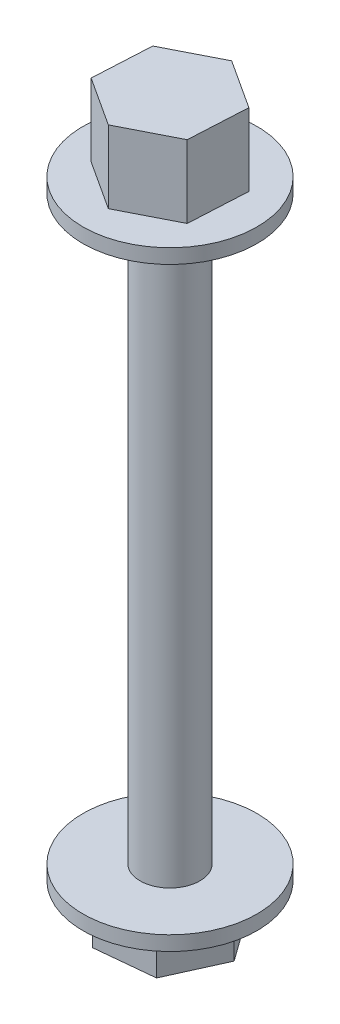
SolidWorks part; units mm, degrees
material "Plain Carbon Steel"
ref_plane "Front Plane" through (0, 0, 0) normal (0, 0, 1) x (1, 0, 0)
ref_plane "Top Plane" through (0, 0, 0) normal (0, 1, 0) x (1, 0, 0)
ref_plane "Right Plane" through (0, 0, 0) normal (1, 0, 0) x (0, 0, -1)
sketch "Sketch1" plane through (0, 0, 0) normal (0, 1, 0) x (1, 0, 0)
  circle A0 centre (0, 0) radius 3.2639
  dimension "D1" = 6.5278
extrude "Boss-Extrude1" add sketch "Sketch1" along normal blind 63.5
sketch "Sketch2" plane through (0, 63.5, 0) normal (0, 1, 0) x (1, 0, 0)
  circle A0 centre (0, 0) radius 9.525
  dimension "D1" = 19.05
extrude "Boss-Extrude2" add sketch "Sketch2" along normal blind 1.5875
sketch "Sketch3" plane through (0, 0, 0) normal (0, -1, 0) x (1, 0, 0)
  circle A0 centre (0, 0) radius 9.525
  dimension "D1" = 19.05
extrude "Boss-Extrude3" add sketch "Sketch3" along normal blind 1.5875
sketch "Sketch4" plane through (0, -1.5875, 0) normal (0, -1, 0) x (1, 0, 0)
  line L1 (3.7399, 5.2131) -> (-2.6447, 5.8453)
  line L2 (-2.6447, 5.8453) -> (-6.3846, 0.6323)
  line L3 (-6.3846, 0.6323) -> (-3.7399, -5.2131)
  line L4 (-3.7399, -5.2131) -> (2.6447, -5.8453)
  line L5 (2.6447, -5.8453) -> (6.3846, -0.6323)
  line L6 (6.3846, -0.6323) -> (3.7399, 5.2131)
  circle A0 centre (0, 0) radius 5.5562 construction
  dimension "D1" = 11.1125
extrude "Boss-Extrude4" add sketch "Sketch4" along normal blind 4.7625
sketch "Sketch5" plane through (0, 65.0875, 0) normal (0, 1, 0) x (1, 0, 0)
  line L1 (5.3794, -3.4964) -> (5.7177, 2.9104)
  line L2 (5.7177, 2.9104) -> (0.3383, 6.4069)
  line L3 (0.3383, 6.4069) -> (-5.3794, 3.4964)
  line L4 (-5.3794, 3.4964) -> (-5.7177, -2.9104)
  line L5 (-5.7177, -2.9104) -> (-0.3383, -6.4069)
  line L6 (-0.3383, -6.4069) -> (5.3794, -3.4964)
  circle A0 centre (0, 0) radius 5.5562 construction
  dimension "D1" = 11.1125
extrude "Boss-Extrude5" add sketch "Sketch5" along normal blind 7.9375
